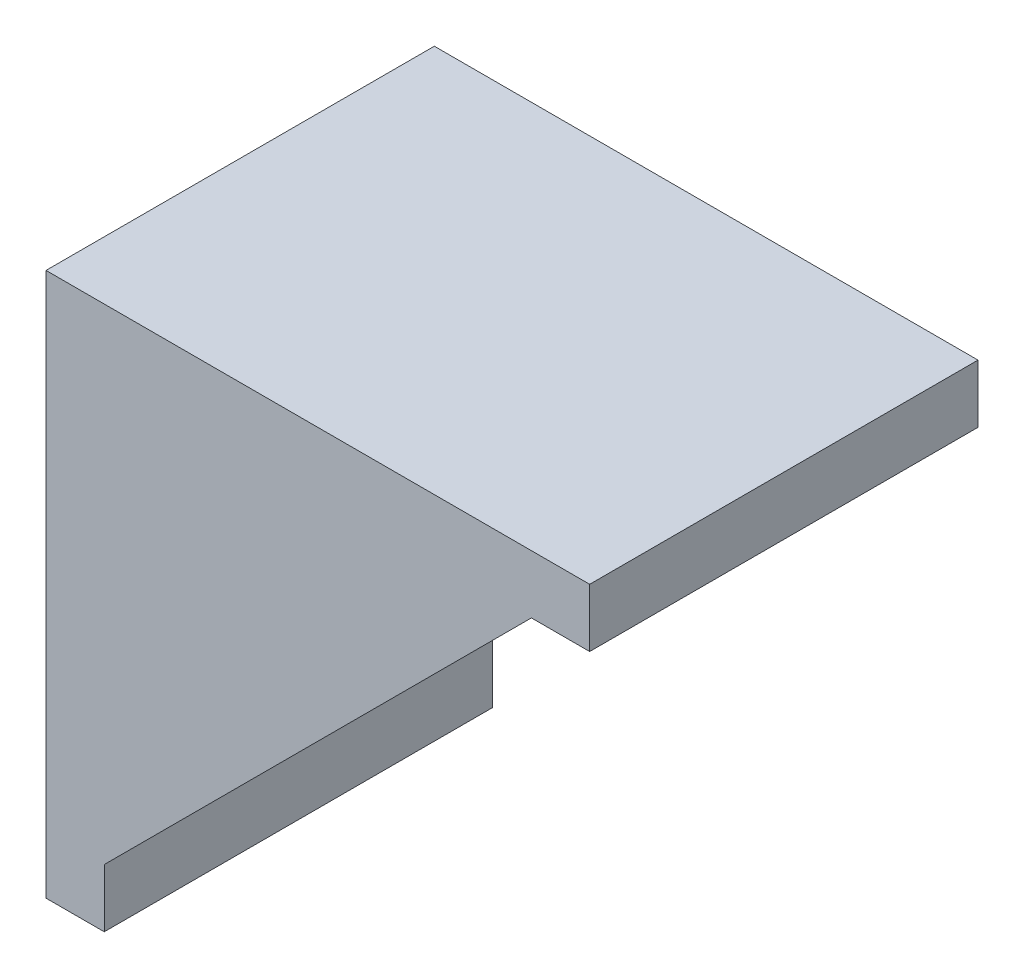
SolidWorks part; units mm, degrees
ref_plane "前基準面" through (0, 0, 0) normal (0, 0, 1) x (1, 0, 0)
ref_plane "上基準面" through (0, 0, 0) normal (0, 1, 0) x (1, 0, 0)
ref_plane "右基準面" through (0, 0, 0) normal (1, 0, 0) x (0, 0, -1)
sketch "草圖1" plane through (0, 0, 0) normal (0, 0, 1) x (1, 0, 0)
  line L0 (-11, -11) -> (11, 11)
  line L1 (-14, 14) -> (14, 14)
  line L2 (-14, 14) -> (-14, -14)
  line L3 (-14, -14) -> (-11, -14)
  line L4 (14, 14) -> (14, 11)
  line L5 (14, 11) -> (11, 11)
  line L6 (-11, -14) -> (-11, -11)
  point P4 (0, 14)
  point P6 (-14, 0)
  dimension "D1" = 28
  dimension "D2" = 28
  dimension "D3" = 3
  dimension "D4" = 3
extrude "填料-伸長1" add sketch "草圖1" along normal blind 20
